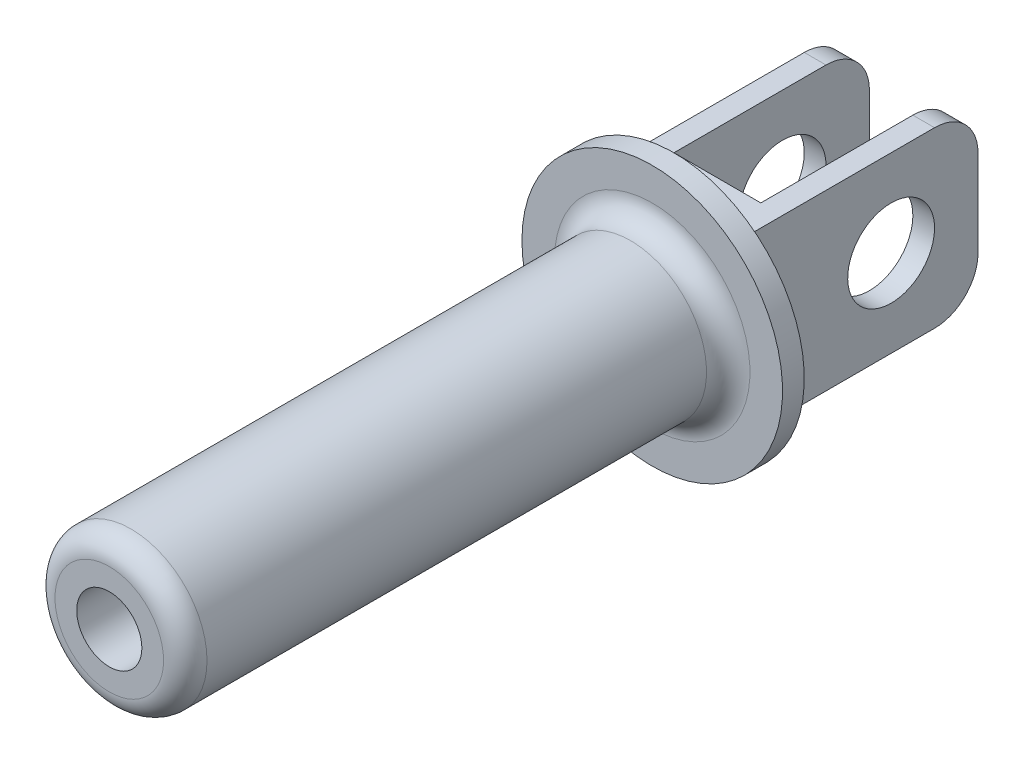
SolidWorks part; units mm, degrees
ref_plane "前视基准面" through (0, 0, 0) normal (0, 0, 1) x (1, 0, 0)
ref_plane "上视基准面" through (0, 0, 0) normal (0, 1, 0) x (1, 0, 0)
ref_plane "右视基准面" through (0, 0, 0) normal (1, 0, 0) x (0, 0, -1)
sketch "草图1" plane through (0, 0, 0) normal (0, 0, 1) x (1, 0, 0)
  circle A0 centre (0, 0) radius 17.5
  dimension "D1" = 35
extrude "凸台-拉伸1" add sketch "草图1" along normal blind 125
sketch "草图2" plane through (0, 0, 0) normal (0, 0, -1) x (-1, 0, 0)
  circle A0 centre (0, 0) radius 30
  dimension "D1" = 60
extrude "凸台-拉伸2" add sketch "草图2" along normal blind 5
sketch "草图4" plane through (0, 0, -5) normal (0, 0, -1) x (-1, 0, 0)
  line L1 (-15, 20) -> (15, 20)
  line L2 (-15, 20) -> (-15, -20)
  line L3 (-15, -20) -> (15, -20)
  line L4 (15, 20) -> (15, -20)
  line L5 (-15, 20) -> (15, -20) construction
  line L6 (-15, -20) -> (15, 20) construction
  point P0 (0, 0)
  dimension "D1" = 30
  dimension "D2" = 40
extrude "凸台-拉伸3" add sketch "草图4" along normal blind 55
sketch "草图7" plane through (15, 0, 0) normal (1, 0, 0) x (0, 0, -1)
  line L0 (60, 20) -> (60, -20) construction
  circle A0 centre (40, 0) radius 10
  dimension "D1" = 20
  dimension "D2" = 20
sketch "草图8" plane through (0, 0, 125) normal (0, 0, 1) x (1, 0, 0)
  circle A0 centre (0, 0) radius 7.5
  dimension "D1" = 15
extrude "切除-拉伸3" cut sketch "草图8" against normal blind 70
sketch "草图9" plane through (0, 0, -60) normal (0, 0, -1) x (-1, 0, 0)
  line L0 (-10, 20) -> (-10, -20)
  line L1 (15, 20) -> (-15, 20) construction
  line L2 (-15, -20) -> (15, -20) construction
  line L3 (-10, -20) -> (10, -20)
  line L4 (10, -20) -> (10, 20)
  line L5 (10, 20) -> (-10, 20)
  dimension "D1" = 10
  dimension "D2" = 10
extrude "切除-拉伸4" cut sketch "草图9" against normal blind 45
extrude "切除-拉伸5" cut sketch "草图7" against normal through all both and the other way through all contours A0
fillet "圆角9" radius 5 1 edges at (-17.5, 0, 0)
fillet "圆角10" radius 5 1 edges at (17.5, 0, 125)
fillet "圆角11" radius 10 4 edges at (12.5, -20, -60) (12.5, 20, -60) (-12.5, 20, -60) (-12.5, -20, -60)
scale "缩放比例1" bodies to scale 113 scale about origin uniform scaling yes scale factor 0.5
